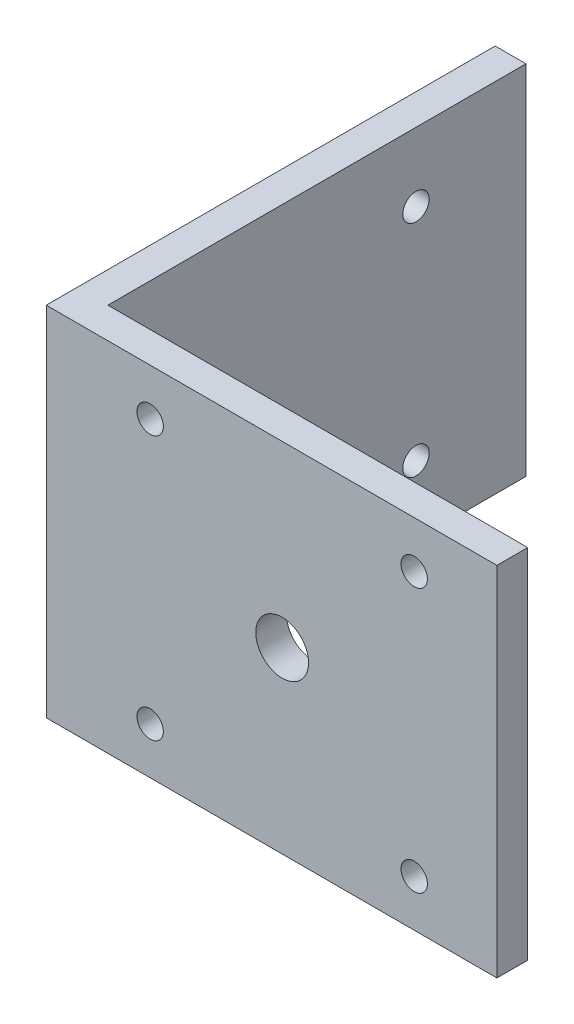
SolidWorks part; units mm, degrees
ref_plane "Front Plane" through (0, 0, 0) normal (0, 0, 1) x (1, 0, 0)
ref_plane "Top Plane" through (0, 0, 0) normal (0, 1, 0) x (1, 0, 0)
ref_plane "Right Plane" through (0, 0, 0) normal (1, 0, 0) x (0, 0, -1)
sketch "Sketch1" plane through (0, 0, 0) normal (0, 1, 0) x (1, 0, 0)
  line L0 (0, 0) -> (0, 51)
  line L1 (0, 51) -> (3.5, 51)
  line L2 (3.5, 51) -> (3.5, 3.5)
  line L3 (3.5, 3.5) -> (51.2, 3.5)
  line L4 (51.2, 3.5) -> (51.2, 0)
  line L5 (51.2, 0) -> (0, 0)
  dimension "D1" = 51.2
  dimension "D2" = 51
  dimension "D3" = 3.5
  dimension "D4" = 3.5
extrude "Boss-Extrude1" add sketch "Sketch1" along normal blind 40.6
sketch "Sketch2" plane through (0, 0, -3.5) normal (0, 0, -1) x (-1, 0, 0)
  line L0 (-6.5, 40.6) -> (-6.5, 0)
  line L1 (-51.2, 40.6) -> (-3.5, 40.6) construction
  line L2 (-51.2, 0) -> (-3.5, 0) construction
  line L3 (-3.5, 40.6) -> (-3.5, 0) construction
  line L4 (-47.1, 40.6) -> (-47.1, 0)
  line L5 (-6.5, 40.6) -> (-47.1, 0) construction
  circle A0 centre (-26.8, 20.3) radius 3
  circle A1 centre (-11.8, 35.3) radius 1.5
  circle A2 centre (-11.8, 5.3) radius 1.5
  circle A3 centre (-41.8, 5.3) radius 1.5
  circle A4 centre (-41.8, 35.3) radius 1.5
  point P23 (-26.8, 20.3)
  dimension "D3" = 6
  dimension "D4" = 3
  dimension "D6" = 30
  dimension "D1" = 3
  dimension "D2" = 40.6
  dimension "D5" = 4
extrude "Cut-Extrude1" cut sketch "Sketch2" against normal through all both and the other way through all contours A1 L5 | L5 A1 | A4 | L5 A0 | A0 L5 | A2 | L5 A3 | A3 L5
sketch "Sketch3" plane through (3.5, 0, 0) normal (1, 0, 0) x (0, 0, -1)
  line L0 (51, 20.3) -> (3.5, 20.3) construction
  line L1 (51, 40.6) -> (51, 0) construction
  line L2 (3.5, 40.6) -> (3.5, 0) construction
  line L3 (51, 32.8) -> (3.5, 32.8)
  circle A0 centre (38.5, 32.8) radius 1.5
  circle A2 centre (8.5, 32.8) radius 1.5
  circle A3 centre (8.5, 7.8) radius 1.5
  circle A4 centre (38.5, 7.8) radius 1.5
  dimension "D1" = 3
  dimension "D2" = 30
  dimension "D3" = 3
  dimension "D4" = 5
  dimension "D5" = 25
extrude "Cut-Extrude2" cut sketch "Sketch3" against normal through all both and the other way through all contours L3 A0 | L3 A0 | L3 A2 | A3 | A4
